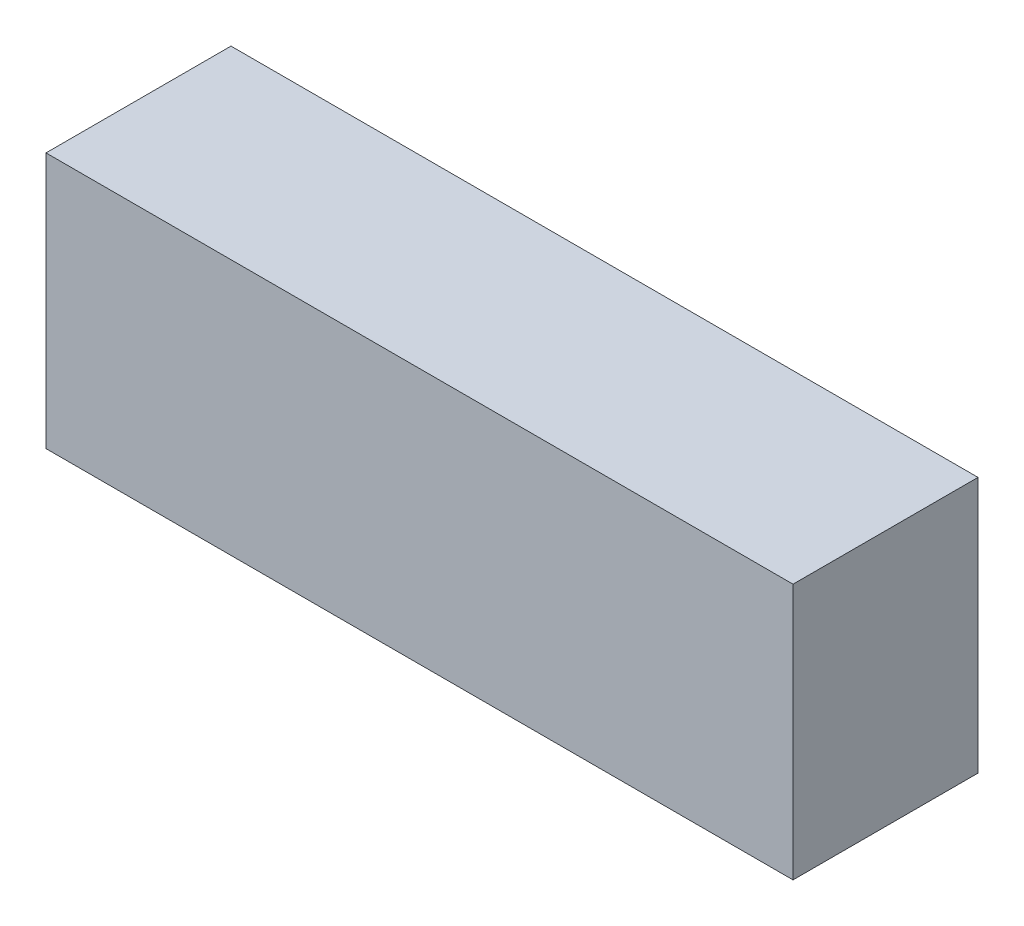
SolidWorks part; units mm, degrees
ref_plane "Front Plane" through (0, 0, 0) normal (0, 0, 1) x (1, 0, 0)
ref_plane "Top Plane" through (0, 0, 0) normal (0, 1, 0) x (1, 0, 0)
ref_plane "Right Plane" through (0, 0, 0) normal (1, 0, 0) x (0, 0, -1)
sketch "Sketch1" plane through (0, 0, 0) normal (0, 0, 1) x (1, 0, 0)
  line L1 (-52.5, -18) -> (52.5, -18)
  line L2 (-52.5, -18) -> (-52.5, 18)
  line L3 (-52.5, 18) -> (52.5, 18)
  line L4 (52.5, -18) -> (52.5, 18)
  line L5 (-52.5, -18) -> (52.5, 18) construction
  line L6 (-52.5, 18) -> (52.5, -18) construction
  point P0 (0, 0)
  dimension "D1" = 105
  dimension "D2" = 36
extrude "Boss-Extrude1" add sketch "Sketch1" along normal blind 26
